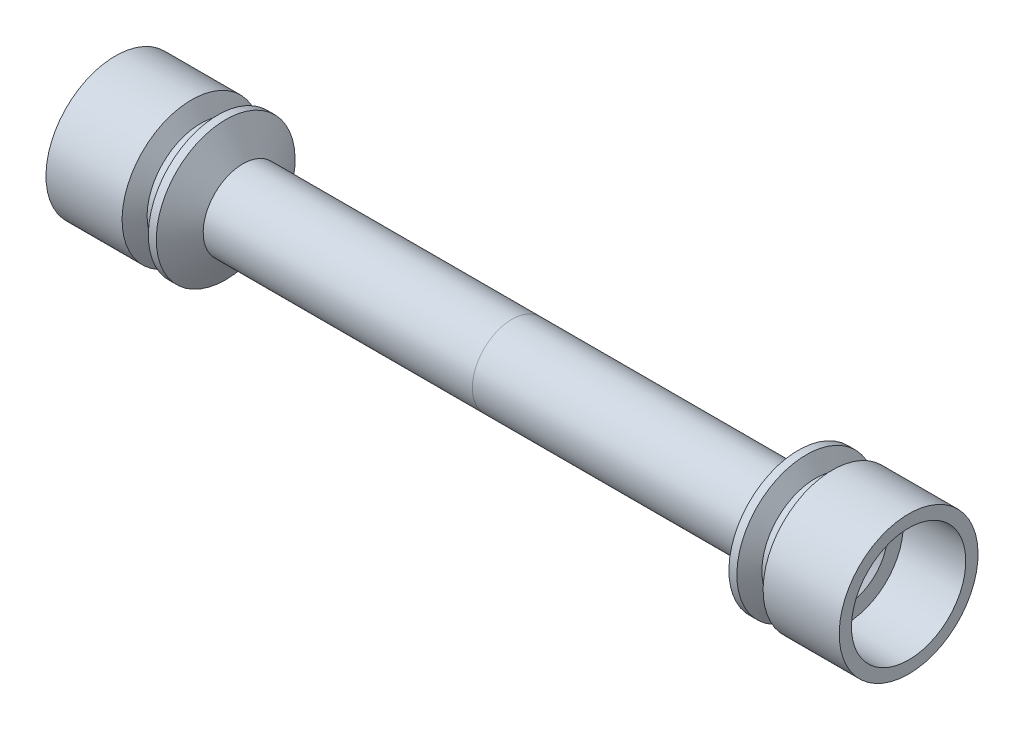
SolidWorks part; units mm, degrees
ref_plane "Front Plane" through (0, 0, 0) normal (0, 0, 1) x (1, 0, 0)
ref_plane "Top Plane" through (0, 0, 0) normal (0, 1, 0) x (1, 0, 0)
ref_plane "Right Plane" through (0, 0, 0) normal (1, 0, 0) x (0, 0, -1)
sketch "Sketch2" plane through (0, 0, 0) normal (0, 0, 1) x (1, 0, 0)
  line L0 (0, 0) -> (0, 28.4375) construction
  line L1 (-31.75, 4.575) -> (-26.75, 4.575) construction
  line L2 (-31.75, 4.575) -> (-31.75, -4.575) construction
  line L3 (-31.75, -4.575) -> (-26.75, -4.575) construction
  line L4 (-26.75, 4.575) -> (-26.75, -4.575) construction
  line L5 (-31.75, 4.575) -> (-26.75, -4.575) construction
  line L6 (-31.75, -4.575) -> (-26.75, 4.575) construction
  line L7 (26.75, 4.5) -> (36.8332, 4.5) construction
  line L8 (26.75, 4.5) -> (26.75, -4.5) construction
  line L9 (26.75, -4.5) -> (36.8332, -4.5) construction
  line L10 (36.8332, 4.5) -> (36.8332, -4.5) construction
  line L11 (26.75, 4.5) -> (36.8332, -4.5) construction
  line L12 (26.75, -4.5) -> (36.8332, 4.5) construction
  line L13 (-31.75, 0) -> (36.8332, 0) construction
  line L14 (-31.75, 5.5562) -> (-25.657, 5.5562)
  line L21 (-21.5457, 3.175) -> (0, 3.175)
  line L22 (-31.75, 5.5562) -> (-31.75, 4.575)
  line L23 (-31.75, 4.575) -> (-26.75, 4.575)
  line L24 (-26.75, 4.575) -> (-26.75, 0)
  line L25 (-26.75, 0) -> (0, 0)
  line L26 (0, 0) -> (0, 3.175)
  line L27 (-33.5594, -5.5562) -> (-33.5594, 5.5562) construction
  line L28 (-25.657, 5.5562) -> (-24.9237, 4.2862)
  line L29 (-24.9237, 4.2862) -> (-24.2888, 4.2862)
  line L30 (-31.75, 5.5562) -> (31.75, 5.5562) construction
  line L31 (0, 1.6) -> (-12.5, 1.6)
  line L32 (-12.5, 1.6) -> (-14.1, 0)
  line L33 (-12.5, 1.6) -> (-12.5, -1.6) construction
  line L34 (-12.5, 1.6) -> (12.5, 1.6) construction
  line L35 (-26.75, 1.7145) -> (-21.925, 1.7145)
  line L36 (-21.925, 1.7145) -> (-21.925, 0)
  line L37 (-26.75, 3.305) -> (-26.242, 2.797)
  line L38 (-21.925, 1.7145) -> (-34.925, 1.7145) construction
  line L39 (-21.925, 1.7145) -> (-21.925, -1.7145) construction
  line L40 (-21.925, -1.7145) -> (-34.925, -1.7145) construction
  line L41 (-34.925, 1.7145) -> (-34.925, -1.7145) construction
  line L42 (-26.242, 2.797) -> (-26.242, 0)
  line L46 (-24.2888, 4.2862) -> (-23.5555, 5.5562)
  line L47 (-23.5555, 5.5562) -> (-22.9205, 5.5562)
  line L48 (-22.9205, 5.5562) -> (-21.5457, 3.175)
  line L49 (-24.6062, 4.2862) -> (-24.6062, 6.3987) construction
  line L50 (-24.6062, 6.3987) -> (24.6062, 6.3987) construction
  point P0 (-29.25, 0)
  point P5 (31.7916, 0)
  point P27 (-33.5594, 0)
  point P28 (-18.8314, 6.3987)
  point P29 (-12.5, 0)
  point P33 (0, 6.3987)
  point P35 (-18.6093, 5.5562)
  point P36 (0, 1.6)
  point P48 (-21.925, 0)
  point P51 (0, 5.5562)
  point P52 (-20.4916, 6.5757)
  dimension "D3" = 3.175
  dimension "D4" = 11.1125
  dimension "D5" = 9.15
  dimension "D6" = 60
  dimension "D7" = 0.635
  dimension "D8" = 60
  dimension "D9" = 49.2125
  dimension "D10" = 1.27
  dimension "D11" = 63.5
  dimension "D12" = 0.635
  dimension "D13" = 45
  dimension "D14" = 25
  dimension "D15" = 3.2
  dimension "D16" = 3.429
  dimension "D17" = 3.175
  dimension "D18" = 1.27
  dimension "D19" = 0.508
  dimension "D20" = 45
  dimension "D21" = 13
  dimension "D22" = 5
revolve "Revolve1" add sketch "Sketch2" angle 360 about L13
mirror "Mirror1" about plane through (0, 0, 0) normal (1, 0, 0) of bodies 101
chamfer "Chamfer1" distance 0.508 angle 45 1 edges at (-31.75, -4.575, 0)
